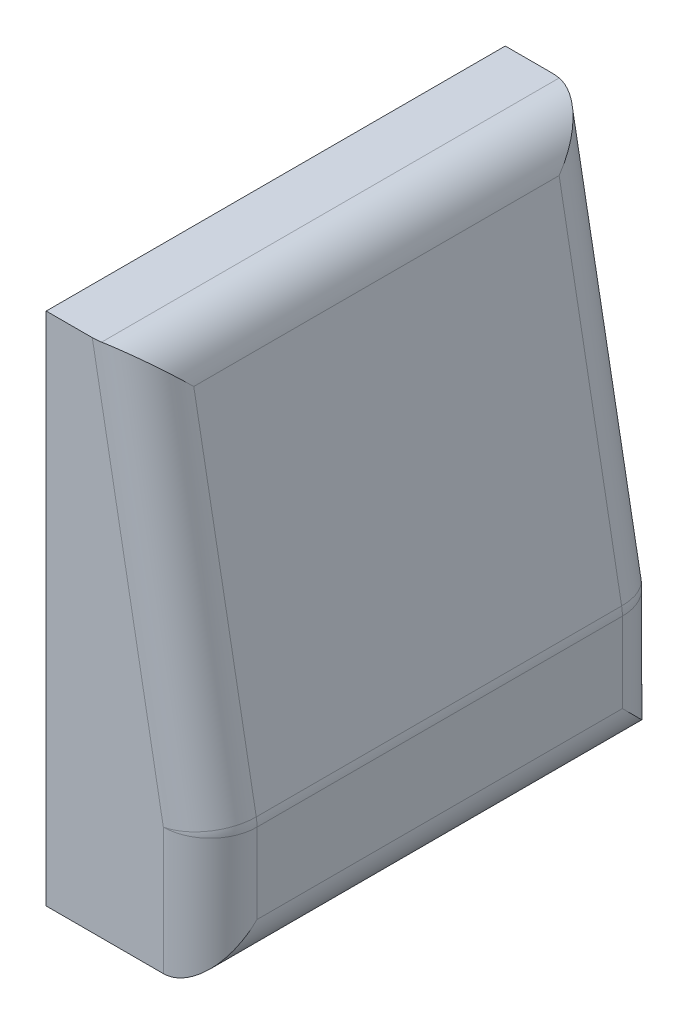
SolidWorks part; units mm, degrees
ref_plane "Front Plane" through (0, 0, 0) normal (0, 0, 1) x (1, 0, 0)
ref_plane "Top Plane" through (0, 0, 0) normal (0, 1, 0) x (1, 0, 0)
ref_plane "Right Plane" through (0, 0, 0) normal (1, 0, 0) x (0, 0, -1)
sketch "Sketch1" plane through (0, 0, 0) normal (0, 0, 1) x (1, 0, 0)
  line L0 (0, 550) -> (0, -550)
  line L1 (0, -550) -> (350, -550)
  line L2 (350, -550) -> (350, -270)
  line L3 (350, -270) -> (200, 550)
  line L4 (200, 550) -> (0, 550)
  point P3 (0, 0)
  dimension "D1" = 350
  dimension "D2" = 200
  dimension "D3" = 1100
  dimension "D4" = 280
extrude "Boss-Extrude1" add sketch "Sketch1" along normal mid plane 980
fillet "Fillet1" radius 100 7 edges at (275, 140, 490) (200, 550, 0) (275, 140, -490) (350, -550, 0) (350, -410, 490) (350, -270, 0) (350, -410, -490)
